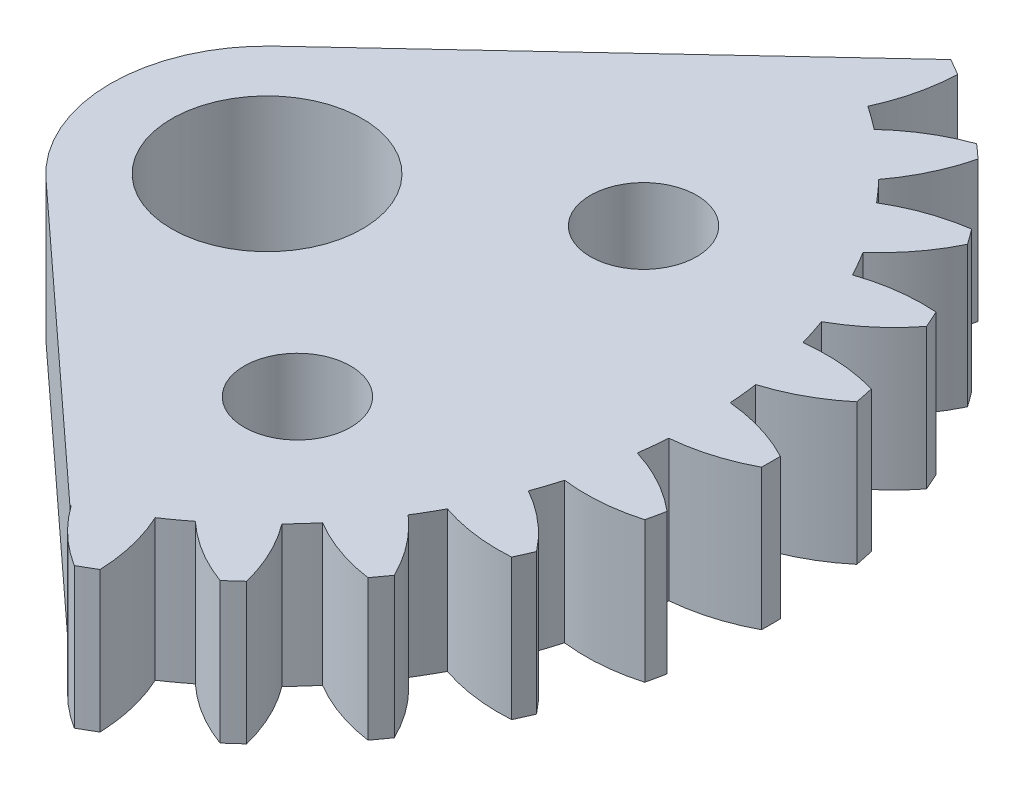
SolidWorks part; units mm, degrees
ref_plane "前视基准面" through (0, 0, 0) normal (0, 0, 1) x (1, 0, 0)
ref_plane "上视基准面" through (0, 0, 0) normal (0, 1, 0) x (1, 0, 0)
ref_plane "右视基准面" through (0, 0, 0) normal (1, 0, 0) x (0, 0, -1)
other "Configuration Table"
sketch "草图1" plane through (0, 0, 0) normal (0, 1, 0) x (1, 0, 0)
  line L0 (8.9628, 20.4663) -> (-13.3857, -0.3977)
  line L1 (5.5049, 17.1913) -> (5.2127, 16.5901)
  line L2 (-20.4818, 9.6015) -> (-16.5616, -7.7073)
  line L3 (-13.3274, -15.071) -> (5.4815, -32.3529)
  circle A0 centre (6.7455, -19.0727) radius 2.6
  circle A1 centre (8.3596, 1.4364) radius 2.6
  circle A2 centre (-6.5616, -7.7073) radius 6.1
  circle A3 centre (-13.1884, 21.5516) radius 6.1
  circle A4 centre (-6.5616, -7.7073) radius 10
  arc A5 (5.4815, -32.3529) -> (5.5389, -32.3248) centre (-6.5616, -7.7073) ccw
  arc A6 (5.5389, -32.3248) -> (8.9628, -35.5516) centre (15.3214, -25.3747) ccw
  arc A7 (8.9628, -35.5516) -> (10.0057, -34.9495) centre (-6.5129, -7.5426) ccw
  arc A8 (10.0057, -34.9495) -> (8.8985, -30.3173) centre (-1.987, -35.3677) ccw
  arc A9 (8.8985, -30.3173) -> (10.3847, -29.2375) centre (-6.5129, -7.5426) ccw
  arc A10 (10.3847, -29.2375) -> (14.448, -31.722) centre (18.5518, -20.4455) ccw
  arc A11 (14.448, -31.722) -> (15.343, -30.9162) centre (-6.5129, -7.5426) ccw
  arc A12 (15.343, -30.9162) -> (13.2968, -26.6154) centre (3.6993, -33.8187) ccw
  arc A13 (13.2968, -26.6154) -> (14.5261, -25.2502) centre (-6.5129, -7.5426) ccw
  arc A14 (14.5261, -25.2502) -> (19.0172, -26.8356) centre (20.6867, -14.9523) ccw
  arc A15 (19.0172, -26.8356) -> (19.725, -25.8613) centre (-6.5129, -7.5426) ccw
  arc A16 (19.725, -25.8613) -> (16.8294, -22.08) centre (8.9392, -31.1213) ccw
  arc A17 (16.8294, -22.08) -> (17.7479, -20.489) centre (-6.5129, -7.5426) ccw
  arc A18 (17.7479, -20.489) -> (22.4705, -21.106) centre (21.6329, -9.1352) ccw
  arc A19 (22.4705, -21.106) -> (22.9603, -20.0058) centre (-6.5129, -7.5426) ccw
  arc A20 (22.9603, -20.0058) -> (19.3418, -16.9091) centre (13.5038, -27.3933) ccw
  arc A21 (19.3418, -16.9091) -> (19.9095, -15.162) centre (-6.5129, -7.5426) ccw
  arc A22 (19.9095, -15.162) -> (24.6571, -14.7836) centre (21.3489, -3.2486) ccw
  arc A23 (24.6571, -14.7836) -> (24.9075, -13.6057) centre (-6.5129, -7.5426) ccw
  arc A24 (24.9075, -13.6057) -> (20.7242, -11.329) centre (17.1936, -22.7979) ccw
  arc A25 (20.7242, -11.329) -> (20.9162, -9.5019) centre (-6.5129, -7.5426) ccw
  arc A26 (20.9162, -9.5019) -> (25.4815, -8.1448) centre (19.8473, 2.4504) ccw
  arc A27 (25.4815, -8.1448) -> (25.4815, -6.9405) centre (-6.5129, -7.5426) ccw
  arc A28 (25.4815, -6.9405) -> (20.9162, -5.5833) centre (19.8473, -17.5356) ccw
  arc A29 (20.9162, -5.5833) -> (20.7242, -3.7563) centre (-6.5129, -7.5426) ccw
  arc A30 (20.7242, -3.7563) -> (24.9075, -1.4796) centre (17.1936, 7.7126) ccw
  arc A31 (24.9075, -1.4796) -> (24.6571, -0.3017) centre (-6.5129, -7.5426) ccw
  arc A32 (24.6571, -0.3017) -> (19.9095, 0.0767) centre (21.3489, -11.8367) ccw
  arc A33 (19.9095, 0.0767) -> (19.3418, 1.8239) centre (-6.5129, -7.5426) ccw
  arc A34 (19.3418, 1.8239) -> (22.9603, 4.9206) centre (13.5038, 12.3081) ccw
  arc A35 (22.9603, 4.9206) -> (22.4705, 6.0207) centre (-6.5129, -7.5426) ccw
  arc A36 (22.4705, 6.0207) -> (17.7479, 5.4037) centre (21.6329, -5.95) ccw
  arc A37 (17.7479, 5.4037) -> (16.8294, 6.9947) centre (-6.5129, -7.5426) ccw
  arc A38 (16.8294, 6.9947) -> (19.725, 10.776) centre (8.9392, 16.036) ccw
  arc A39 (19.725, 10.776) -> (19.0172, 11.7503) centre (-6.5129, -7.5426) ccw
  arc A40 (19.0172, 11.7503) -> (14.5261, 10.1649) centre (20.6867, -0.133) ccw
  arc A41 (14.5261, 10.1649) -> (13.2968, 11.5301) centre (-6.5129, -7.5426) ccw
  arc A42 (13.2968, 11.5301) -> (15.343, 15.8309) centre (3.6993, 18.7334) ccw
  arc A43 (15.343, 15.8309) -> (14.448, 16.6367) centre (-6.5129, -7.5426) ccw
  arc A44 (14.448, 16.6367) -> (10.3847, 14.1522) centre (18.5518, 5.3602) ccw
  arc A45 (10.3847, 14.1522) -> (8.8985, 15.232) centre (-6.5129, -7.5426) ccw
  arc A46 (8.8985, 15.232) -> (10.0057, 19.8642) centre (-1.987, 20.2825) ccw
  arc A47 (10.0057, 19.8642) -> (8.9628, 20.4663) centre (-6.5129, -7.5426) ccw
  arc A48 (8.9628, 20.4663) -> (5.5049, 17.1913) centre (15.3214, 10.2895) ccw
  arc A49 (5.2127, 16.5901) -> (0.4448, 18.3678) centre (-6.5616, -7.7073) ccw
  arc A50 (0.4448, 18.3678) -> (-20.4818, 9.6015) centre (-13.1884, 21.5516) ccw
  arc A51 (-16.5616, -7.7073) -> (-13.3274, -15.071) centre (-6.5616, -7.7073) ccw
extrude "凸台-拉伸1" add sketch "草图1" along normal blind 9 contours L1 A49 L0 A4 L3 A5 A6 A7 A8 A9 A10 A11 A12 A13 A14 A15 A16 A17 A18 A19 A20 A21 A22 A23 A24 A25 A26 A27 A28 A29 A30 A31 A32 A33 A34 A35 A36 A37 A38 A39 A40 A41 A42 A43 A44 A45 A46 A47 A48 | A4 A2 | A49 L1 A48 L0
sketch "草图2" plane through (0, 9, 0) normal (0, 1, 0) x (1, 0, 0)
  line L2 (8.9628, 20.4663) -> (-13.3857, -0.3977)
  line L3 (-13.3274, -15.071) -> (5.4815, -32.3529)
  line L4 (8.9628, 20.4663) -> (-13.3857, -0.3977)
  line L5 (-13.3274, -15.071) -> (5.4815, -32.3529)
  circle A0 centre (8.3596, 1.4364) radius 2.6 construction
  circle A1 centre (8.3596, 1.4364) radius 2.6
  circle A2 centre (6.7455, -19.0727) radius 2.6 construction
  circle A3 centre (6.7455, -19.0727) radius 2.6
  circle A4 centre (8.3596, 1.4364) radius 3.4
  circle A5 centre (6.7455, -19.0727) radius 3.4
  arc A44 (10.0057, 19.8642) -> (8.9628, 20.4663) centre (-6.5129, -7.5426) ccw
  arc A45 (-13.3857, -0.3977) -> (-13.3274, -15.071) centre (-6.5616, -7.7073) ccw
  arc A46 (5.4815, -32.3529) -> (5.5389, -32.3248) centre (-6.5616, -7.7073) ccw
  arc A47 (5.5389, -32.3248) -> (8.9628, -35.5516) centre (15.3214, -25.3747) ccw
  arc A48 (8.9628, -35.5516) -> (10.0057, -34.9495) centre (-6.5129, -7.5426) ccw
  arc A49 (10.0057, -34.9495) -> (8.8985, -30.3173) centre (-1.987, -35.3677) ccw
  arc A50 (8.8985, -30.3173) -> (10.3847, -29.2375) centre (-6.5129, -7.5426) ccw
  arc A51 (10.3847, -29.2375) -> (14.448, -31.722) centre (18.5518, -20.4455) ccw
  arc A52 (14.448, -31.722) -> (15.343, -30.9162) centre (-6.5129, -7.5426) ccw
  arc A53 (15.343, -30.9162) -> (13.2968, -26.6154) centre (3.6993, -33.8187) ccw
  arc A54 (13.2968, -26.6154) -> (14.5261, -25.2502) centre (-6.5129, -7.5426) ccw
  arc A55 (14.5261, -25.2502) -> (19.0172, -26.8356) centre (20.6867, -14.9523) ccw
  arc A56 (19.0172, -26.8356) -> (19.725, -25.8613) centre (-6.5129, -7.5426) ccw
  arc A57 (19.725, -25.8613) -> (16.8294, -22.08) centre (8.9392, -31.1213) ccw
  arc A58 (16.8294, -22.08) -> (17.7479, -20.489) centre (-6.5129, -7.5426) ccw
  arc A59 (17.7479, -20.489) -> (22.4705, -21.106) centre (21.6329, -9.1352) ccw
  arc A60 (22.4705, -21.106) -> (22.9603, -20.0058) centre (-6.5129, -7.5426) ccw
  arc A61 (22.9603, -20.0058) -> (19.3418, -16.9091) centre (13.5038, -27.3933) ccw
  arc A62 (19.3418, -16.9091) -> (19.9095, -15.162) centre (-6.5129, -7.5426) ccw
  arc A63 (19.9095, -15.162) -> (24.6571, -14.7836) centre (21.3489, -3.2486) ccw
  arc A64 (24.6571, -14.7836) -> (24.9075, -13.6057) centre (-6.5129, -7.5426) ccw
  arc A65 (24.9075, -13.6057) -> (20.7242, -11.329) centre (17.1936, -22.7979) ccw
  arc A66 (20.7242, -11.329) -> (20.9162, -9.5019) centre (-6.5129, -7.5426) ccw
  arc A67 (20.9162, -9.5019) -> (25.4815, -8.1448) centre (19.8473, 2.4504) ccw
  arc A68 (25.4815, -8.1448) -> (25.4815, -6.9405) centre (-6.5129, -7.5426) ccw
  arc A69 (25.4815, -6.9405) -> (20.9162, -5.5833) centre (19.8473, -17.5356) ccw
  arc A70 (20.9162, -5.5833) -> (20.7242, -3.7563) centre (-6.5129, -7.5426) ccw
  arc A71 (20.7242, -3.7563) -> (24.9075, -1.4796) centre (17.1936, 7.7126) ccw
  arc A72 (24.9075, -1.4796) -> (24.6571, -0.3017) centre (-6.5129, -7.5426) ccw
  arc A73 (24.6571, -0.3017) -> (19.9095, 0.0767) centre (21.3489, -11.8367) ccw
  arc A74 (19.9095, 0.0767) -> (19.3418, 1.8239) centre (-6.5129, -7.5426) ccw
  arc A75 (19.3418, 1.8239) -> (22.9603, 4.9206) centre (13.5038, 12.3081) ccw
  arc A76 (22.9603, 4.9206) -> (22.4705, 6.0207) centre (-6.5129, -7.5426) ccw
  arc A77 (22.4705, 6.0207) -> (17.7479, 5.4037) centre (21.6329, -5.95) ccw
  arc A78 (17.7479, 5.4037) -> (16.8294, 6.9947) centre (-6.5129, -7.5426) ccw
  arc A79 (16.8294, 6.9947) -> (19.725, 10.776) centre (8.9392, 16.036) ccw
  arc A80 (19.725, 10.776) -> (19.0172, 11.7503) centre (-6.5129, -7.5426) ccw
  arc A81 (19.0172, 11.7503) -> (14.5261, 10.1649) centre (20.6867, -0.133) ccw
  arc A82 (14.5261, 10.1649) -> (13.2968, 11.5301) centre (-6.5129, -7.5426) ccw
  arc A83 (13.2968, 11.5301) -> (15.343, 15.8309) centre (3.6993, 18.7334) ccw
  arc A84 (15.343, 15.8309) -> (14.448, 16.6367) centre (-6.5129, -7.5426) ccw
  arc A85 (14.448, 16.6367) -> (10.3847, 14.1522) centre (18.5518, 5.3602) ccw
  arc A86 (10.3847, 14.1522) -> (8.8985, 15.232) centre (-6.5129, -7.5426) ccw
  arc A87 (8.8985, 15.232) -> (10.0057, 19.8642) centre (-1.987, 20.2825) ccw
  arc A88 (10.0057, 19.8642) -> (8.9628, 20.4663) centre (-6.5129, -7.5426) ccw
  arc A89 (-13.3857, -0.3977) -> (-13.3274, -15.071) centre (-6.5616, -7.7073) ccw
  arc A90 (5.4815, -32.3529) -> (5.5389, -32.3248) centre (-6.5616, -7.7073) ccw
  arc A91 (5.5389, -32.3248) -> (8.9628, -35.5516) centre (15.3214, -25.3747) ccw
  arc A92 (8.9628, -35.5516) -> (10.0057, -34.9495) centre (-6.5129, -7.5426) ccw
  arc A93 (10.0057, -34.9495) -> (8.8985, -30.3173) centre (-1.987, -35.3677) ccw
  arc A94 (8.8985, -30.3173) -> (10.3847, -29.2375) centre (-6.5129, -7.5426) ccw
  arc A95 (10.3847, -29.2375) -> (14.448, -31.722) centre (18.5518, -20.4455) ccw
  arc A96 (14.448, -31.722) -> (15.343, -30.9162) centre (-6.5129, -7.5426) ccw
  arc A97 (15.343, -30.9162) -> (13.2968, -26.6154) centre (3.6993, -33.8187) ccw
  arc A98 (13.2968, -26.6154) -> (14.5261, -25.2502) centre (-6.5129, -7.5426) ccw
  arc A99 (14.5261, -25.2502) -> (19.0172, -26.8356) centre (20.6867, -14.9523) ccw
  arc A100 (19.0172, -26.8356) -> (19.725, -25.8613) centre (-6.5129, -7.5426) ccw
  arc A101 (19.725, -25.8613) -> (16.8294, -22.08) centre (8.9392, -31.1213) ccw
  arc A102 (16.8294, -22.08) -> (17.7479, -20.489) centre (-6.5129, -7.5426) ccw
  arc A103 (17.7479, -20.489) -> (22.4705, -21.106) centre (21.6329, -9.1352) ccw
  arc A104 (22.4705, -21.106) -> (22.9603, -20.0058) centre (-6.5129, -7.5426) ccw
  arc A105 (22.9603, -20.0058) -> (19.3418, -16.9091) centre (13.5038, -27.3933) ccw
  arc A106 (19.3418, -16.9091) -> (19.9095, -15.162) centre (-6.5129, -7.5426) ccw
  arc A107 (19.9095, -15.162) -> (24.6571, -14.7836) centre (21.3489, -3.2486) ccw
  arc A108 (24.6571, -14.7836) -> (24.9075, -13.6057) centre (-6.5129, -7.5426) ccw
  arc A109 (24.9075, -13.6057) -> (20.7242, -11.329) centre (17.1936, -22.7979) ccw
  arc A110 (20.7242, -11.329) -> (20.9162, -9.5019) centre (-6.5129, -7.5426) ccw
  arc A111 (20.9162, -9.5019) -> (25.4815, -8.1448) centre (19.8473, 2.4504) ccw
  arc A112 (25.4815, -8.1448) -> (25.4815, -6.9405) centre (-6.5129, -7.5426) ccw
  arc A113 (25.4815, -6.9405) -> (20.9162, -5.5833) centre (19.8473, -17.5356) ccw
  arc A114 (20.9162, -5.5833) -> (20.7242, -3.7563) centre (-6.5129, -7.5426) ccw
  arc A115 (20.7242, -3.7563) -> (24.9075, -1.4796) centre (17.1936, 7.7126) ccw
  arc A116 (24.9075, -1.4796) -> (24.6571, -0.3017) centre (-6.5129, -7.5426) ccw
  arc A117 (24.6571, -0.3017) -> (19.9095, 0.0767) centre (21.3489, -11.8367) ccw
  arc A118 (19.9095, 0.0767) -> (19.3418, 1.8239) centre (-6.5129, -7.5426) ccw
  arc A119 (19.3418, 1.8239) -> (22.9603, 4.9206) centre (13.5038, 12.3081) ccw
  arc A120 (22.9603, 4.9206) -> (22.4705, 6.0207) centre (-6.5129, -7.5426) ccw
  arc A121 (22.4705, 6.0207) -> (17.7479, 5.4037) centre (21.6329, -5.95) ccw
  arc A122 (17.7479, 5.4037) -> (16.8294, 6.9947) centre (-6.5129, -7.5426) ccw
  arc A123 (16.8294, 6.9947) -> (19.725, 10.776) centre (8.9392, 16.036) ccw
  arc A124 (19.725, 10.776) -> (19.0172, 11.7503) centre (-6.5129, -7.5426) ccw
  arc A125 (19.0172, 11.7503) -> (14.5261, 10.1649) centre (20.6867, -0.133) ccw
  arc A126 (14.5261, 10.1649) -> (13.2968, 11.5301) centre (-6.5129, -7.5426) ccw
  arc A127 (13.2968, 11.5301) -> (15.343, 15.8309) centre (3.6993, 18.7334) ccw
  arc A128 (15.343, 15.8309) -> (14.448, 16.6367) centre (-6.5129, -7.5426) ccw
  arc A129 (14.448, 16.6367) -> (10.3847, 14.1522) centre (18.5518, 5.3602) ccw
  arc A130 (10.3847, 14.1522) -> (8.8985, 15.232) centre (-6.5129, -7.5426) ccw
  arc A131 (8.8985, 15.232) -> (10.0057, 19.8642) centre (-1.987, 20.2825) ccw
  circle M94 centre (6.7455, -19.0727) radius 2.6
  circle M95 centre (8.3596, 1.4364) radius 2.6
  dimension "D2" = 6.8
  dimension "D3" = 6.8
  dimension "D1" = 0
extrude "切除-拉伸1" cut sketch "草图2" against normal blind 10 contours A4 M95 | A5 M94
